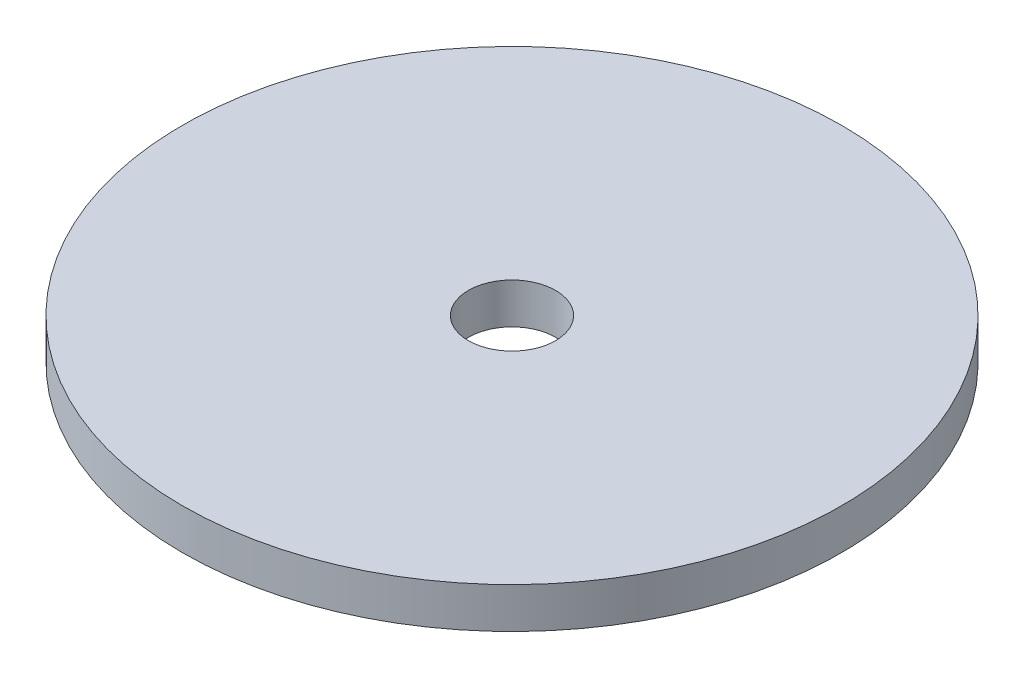
SolidWorks part; units mm, degrees
ref_plane "Front Plane" through (0, 0, 0) normal (0, 0, 1) x (1, 0, 0)
ref_plane "Top Plane" through (0, 0, 0) normal (0, 1, 0) x (1, 0, 0)
ref_plane "Right Plane" through (0, 0, 0) normal (1, 0, 0) x (0, 0, -1)
sketch "Sketch1" plane through (0, 0, 0) normal (0, 1, 0) x (1, 0, 0)
  circle A0 centre (0, 0) radius 19.304
  dimension "D1" = 38.608
extrude "Boss-Extrude1" add sketch "Sketch1" along normal mid plane 2.3813
hole_wizard "#10 Clearance Hole1" positions "Sketch2" profile "Sketch3" hole size "#10" standard "ANSI Inch" end condition through all
sketch "Sketch2" plane through (0, 1.1906, 0) normal (0, 1, 0) x (1, 0, 0)
  point P0 (0, 0)
sketch "Sketch3" plane through (0, 1.1906, 0) normal (1, 0, 0) x (0, 0, 1)
  line L0 (0, 0) -> (0, 2.3812)
  line L1 (0, 2.3812) -> (2.5527, 2.3812)
  line L2 (2.5527, 2.3812) -> (2.5527, 0)
  line L5 (2.5527, 0) -> (0, 0)
  line L11 (0, -6.35) -> (0, 107.95) construction
  dimension "Thru Hole Dia." = 5.1054
  dimension "Thru Hole Depth" = 2.3813
